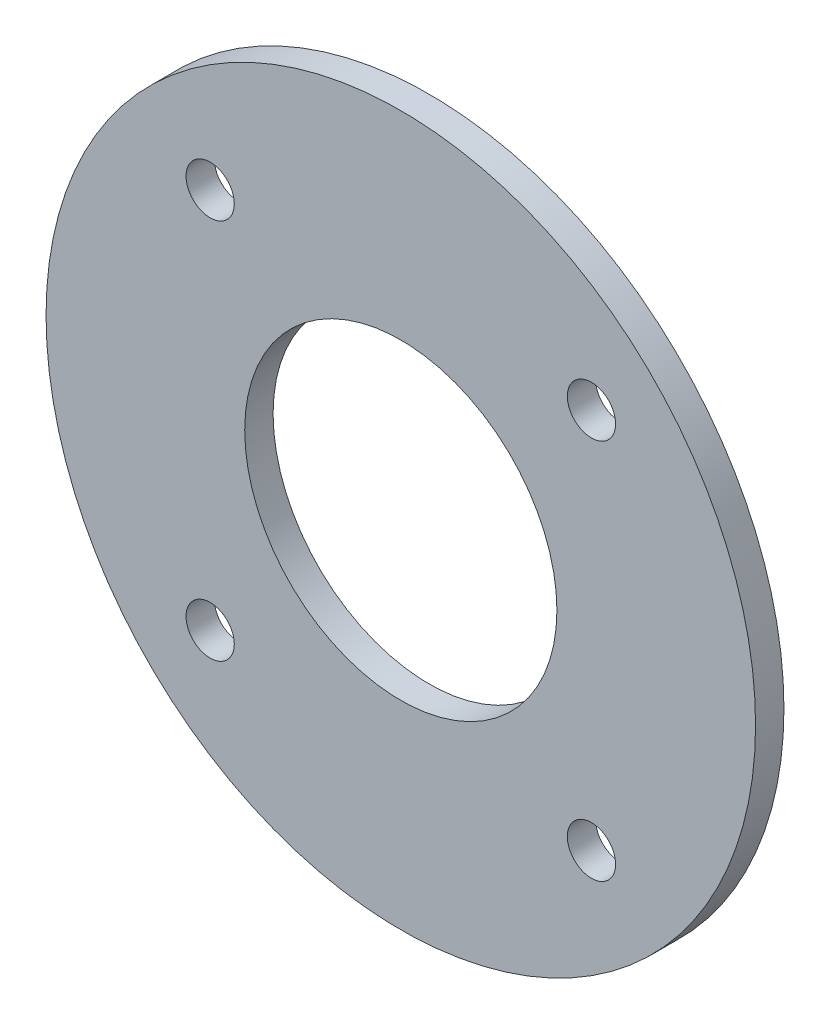
SolidWorks part; units mm, degrees
ref_plane "Plan de face" through (0, 0, 0) normal (0, 0, 1) x (1, 0, 0)
ref_plane "Plan de dessus" through (0, 0, 0) normal (0, 1, 0) x (1, 0, 0)
ref_plane "Plan de droite" through (0, 0, 0) normal (1, 0, 0) x (0, 0, -1)
sketch "Esquisse1" plane through (0, 0, 0) normal (0, 0, 1) x (1, 0, 0)
  circle A0 centre (0, 0) radius 25
  circle A1 centre (-13.435, 13.435) radius 1.7
  circle A2 centre (13.435, 13.435) radius 1.7
  circle A3 centre (13.435, -13.435) radius 1.7
  circle A4 centre (-13.435, -13.435) radius 1.7
  point P19 (0, 0)
  dimension "D1" = 50
  dimension "D5" = 19
  dimension "D6" = 3.4
  dimension "D4" = 4
extrude "Boss.-Extru.1" add sketch "Esquisse1" along normal blind 2 and the other way blind 0.0001
sketch "Esquisse2" plane through (0, 0, -0.0001) normal (0, 0, -1) x (-1, 0, 0)
  circle A0 centre (0, 0) radius 11
extrude "Enlèv. mat.-Extru.1" cut sketch "Esquisse2" against normal blind 10
